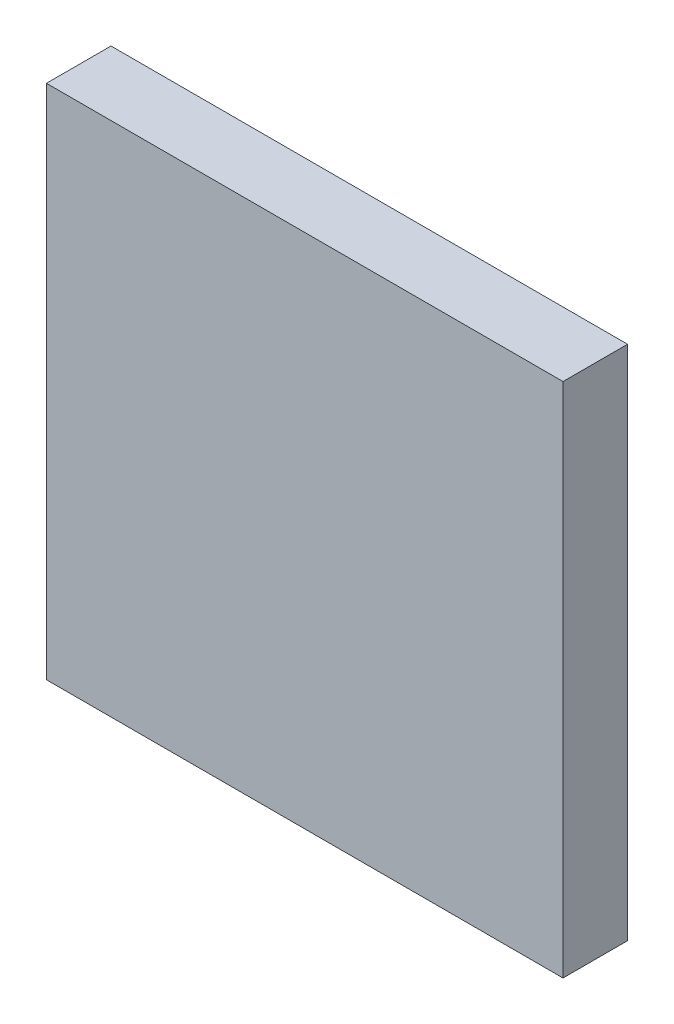
SolidWorks part; units mm, degrees
ref_plane "Front Plane" through (0, 0, 0) normal (0, 0, 1) x (1, 0, 0)
ref_plane "Top Plane" through (0, 0, 0) normal (0, 1, 0) x (1, 0, 0)
ref_plane "Right Plane" through (0, 0, 0) normal (1, 0, 0) x (0, 0, -1)
sketch "Sketch1" plane through (0, 0, 0) normal (0, 1, 0) x (1, 0, 0)
  line L1 (-20, 2.5) -> (20, 2.5)
  line L2 (-20, 2.5) -> (-20, -2.5)
  line L3 (-20, -2.5) -> (20, -2.5)
  line L4 (20, 2.5) -> (20, -2.5)
  line L5 (-20, 2.5) -> (20, -2.5) construction
  line L6 (-20, -2.5) -> (20, 2.5) construction
  point P0 (0, 0)
  dimension "D1" = 40
  dimension "D2" = 5
extrude "Boss-Extrude1" add sketch "Sketch1" along normal blind 40
sketch "Sketch2" plane through (0, 0, 0) normal (0, -1, 0) x (1, 0, 0)
  line L0 (-20, 0) -> (-12, 0) construction
  line L1 (-20, -2.5) -> (-20, 2.5) construction
  line L2 (12, 0) -> (20, 0) construction
  line L3 (20, 2.5) -> (20, -2.5) construction
  circle A0 centre (-12, 0) radius 1.5
  circle A1 centre (12, 0) radius 1.5
  dimension "D1" = 3
  dimension "D2" = 8
extrude "Cut-Extrude1" cut sketch "Sketch2" against normal blind 15
